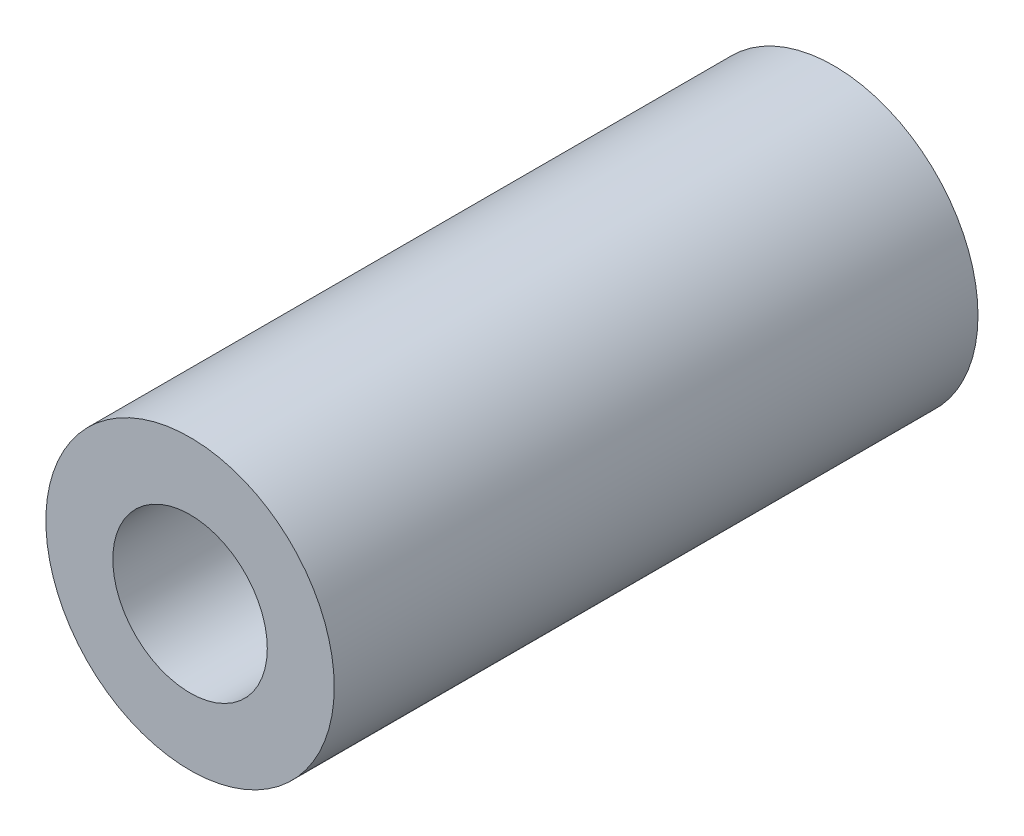
SolidWorks part; units mm, degrees
material "ABS"
ref_plane "Plan de face" through (0, 0, 0) normal (0, 0, 1) x (1, 0, 0)
ref_plane "Plan de dessus" through (0, 0, 0) normal (0, 1, 0) x (1, 0, 0)
ref_plane "Plan de droite" through (0, 0, 0) normal (1, 0, 0) x (0, 0, -1)
sketch "Esquisse1" plane through (0, 0, 0) normal (0, 0, 1) x (1, 0, 0)
  circle A0 centre (0, 0) radius 1.5
  circle A1 centre (0, 0) radius 2.8
  dimension "D1" = 3
  dimension "D2" = 1.3
extrude "Boss.-Extru.1" add sketch "Esquisse1" along normal blind 12.5
